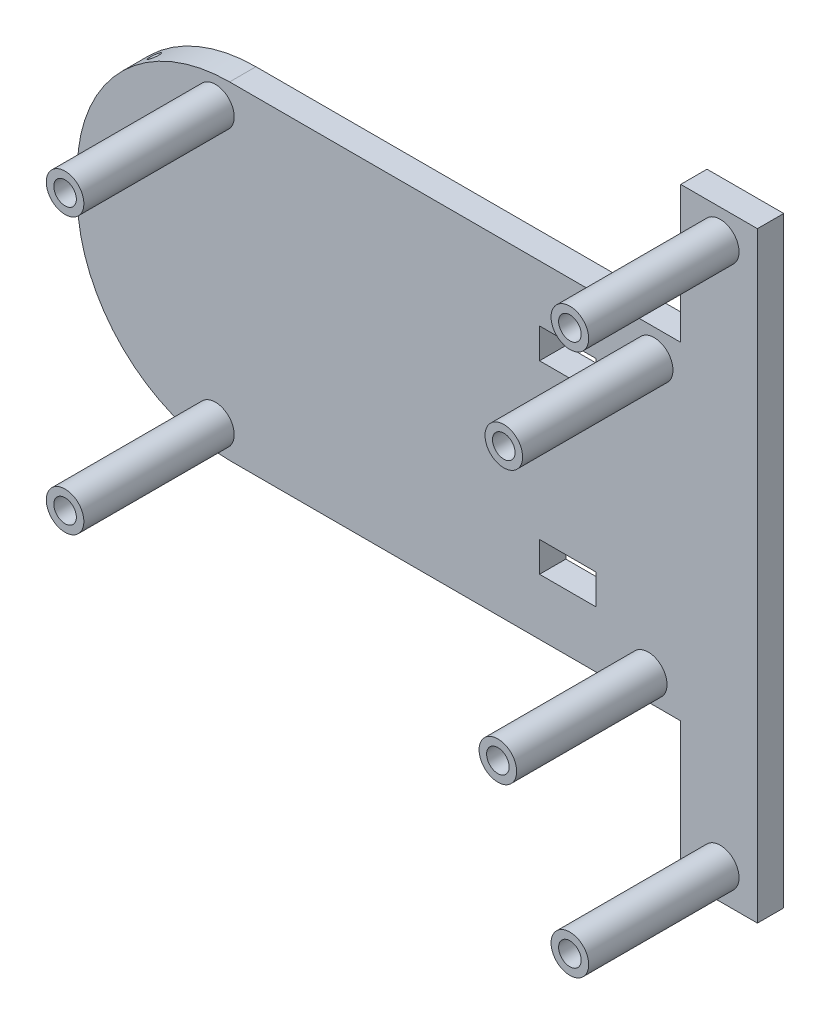
SolidWorks part; units mm, degrees
ref_plane "Plan de face" through (0, 0, 0) normal (0, 0, 1) x (1, 0, 0)
ref_plane "Plan de dessus" through (0, 0, 0) normal (0, 1, 0) x (1, 0, 0)
ref_plane "Plan de droite" through (0, 0, 0) normal (1, 0, 0) x (0, 0, -1)
sketch "Esquisse1" plane through (0, 0, 0) normal (0, 0, 1) x (1, 0, 0)
  line L7 (-20.4048, 60.8522) -> (-20.4048, 43.608)
  line L11 (-42.9128, 28.608) -> (-42.9128, 20.5821)
  line L12 (-42.9128, 20.5821) -> (-57.9614, 20.5821)
  line L13 (-57.9614, 20.5821) -> (-57.9614, 28.608)
  line L15 (-57.9614, 28.608) -> (-42.9128, 28.608)
  line L16 (-20.4048, 43.608) -> (-140.4048, 43.608)
  line L25 (-20.4048, 60.8522) -> (-20.4048, 80)
  line L27 (0, 80) -> (-20.4048, 80)
  line L33 (0, -80) -> (0, 80)
  line L34 (-57.9614, -20.5821) -> (-57.9614, -28.608)
  line L35 (-42.9128, -20.5821) -> (-57.9614, -20.5821)
  line L36 (-42.9128, -28.608) -> (-42.9128, -20.5821)
  line L37 (-57.9614, -28.608) -> (-42.9128, -28.608)
  line L38 (-20.4048, -43.608) -> (-140.4048, -43.608)
  line L39 (-20.4048, -60.8522) -> (-20.4048, -43.608)
  line L40 (-20.4048, -60.8522) -> (-20.4048, -80)
  line L41 (0, -80) -> (-20.4048, -80)
  arc A0 (-140.4048, 43.608) -> (-180.7891, 0) centre (-140.4048, 3.1046) ccw
  arc A1 (-140.4048, -43.608) -> (-180.7891, 0) centre (-140.4048, -3.1046) cw
  dimension "D2" = 120
extrude "Boss.-Extru.2" add sketch "Esquisse1" along normal blind 7
ref_plane "Plan1" through (-170.1225, 30.6253, 0) normal (-0.7337, 0.6795, 0) x (0, 0, 1)
sketch "Esquisse2" plane through (-170.1225, 30.6253, 0) normal (-0.7337, 0.6795, 0) x (0, 0, 1)
  line L0 (7, -29.7176) -> (0, -29.7176) construction
  circle A1 centre (3.5667, 8.2824) radius 1.5
  circle A2 centre (3.5667, -21.7176) radius 1.5
  circle A3 centre (3.5667, -11.7176) radius 1.5
  point P5 (3.5667, -14.0974)
  dimension "D1" = 8
  dimension "D3" = 10
  dimension "D2" = 30
extrude "Enlèv. mat.-Extru.1" cut sketch "Esquisse2" against normal blind 22
ref_plane "Plan2" through (-170.1225, -30.6253, 7) normal (-0.7337, -0.6795, 0) x (0, 0, 1)
sketch "Esquisse7" plane through (-170.1225, -30.6253, 7) normal (-0.7337, -0.6795, 0) x (0, 0, 1)
  line L0 (0, 29.7176) -> (-7, 29.7176) construction
  circle A0 centre (-3.4819, 21.7176) radius 1.5
  circle A1 centre (-3.4819, -8.2824) radius 1.5
  circle A2 centre (-3.4819, 11.7176) radius 1.5
  point P8 (0, 0)
  dimension "D1" = 8
  dimension "D2" = 30
  dimension "D3" = 10
extrude "Enlèv. mat.-Extru.2" cut sketch "Esquisse7" against normal blind 22
sketch "Esquisse8" plane through (0, 0, 7) normal (0, 0, 1) x (1, 0, 0)
  circle A0 centre (-9.8906, 72.2136) radius 3
  circle A1 centre (-9.8906, 72.2136) radius 5
  circle A2 centre (-9.8906, -71.9919) radius 3
  circle A3 centre (-9.8906, -71.9919) radius 5
  circle A4 centre (-27.4656, 36.1622) radius 3
  circle A5 centre (-27.4656, 36.1622) radius 5
  circle A6 centre (-29.0429, -37.0671) radius 3
  circle A7 centre (-29.0429, -37.0671) radius 5
  circle A12 centre (-144.182, 36.1622) radius 3
  circle A13 centre (-144.182, 36.1622) radius 5
  circle A14 centre (-144.182, -37.0671) radius 3
  circle A15 centre (-144.182, -37.0671) radius 5
extrude "Boss.-Extru.3" add sketch "Esquisse8" along normal blind 40
